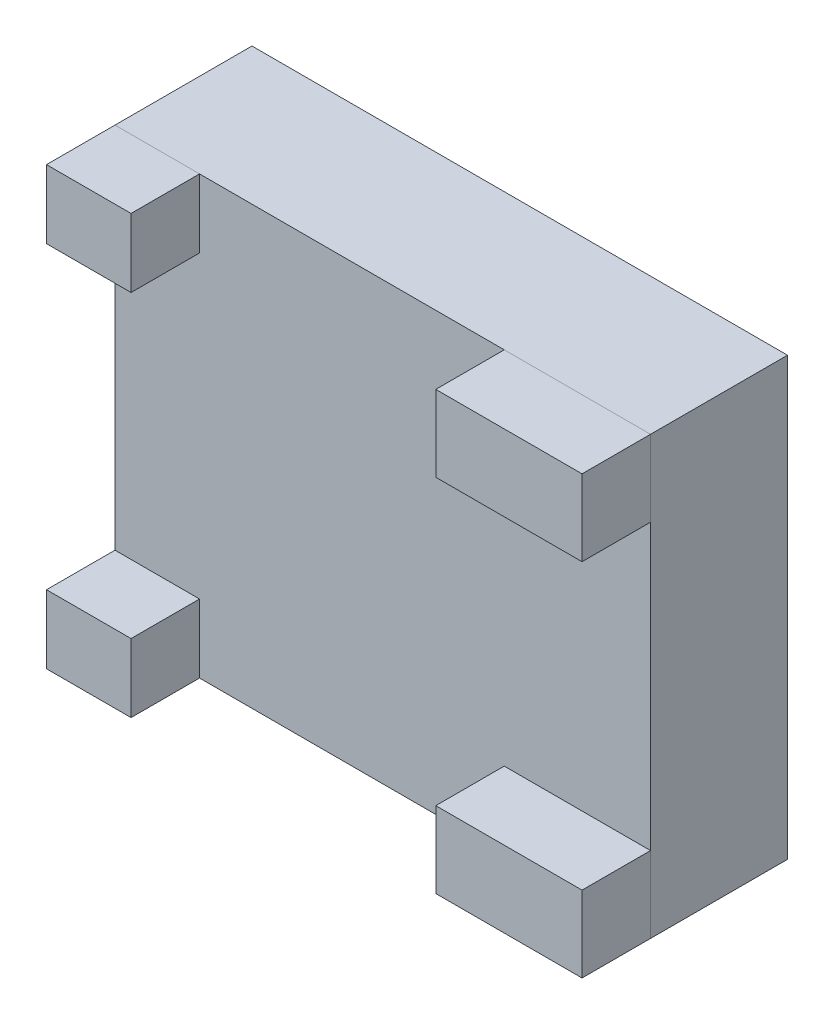
SolidWorks part; units mm, degrees
other "A"
other "B"
other "corpo 3"
other "C" parameters "Espessura"=2
material "AISI 1020"
ref_plane "Plano superior" through (0, 0, 0) normal (0, 0, 1) x (1, 0, 0)
ref_plane "Plano frontal" through (0, 0, 0) normal (0, 1, 0) x (1, 0, 0)
ref_plane "Plano direito" through (0, 0, 0) normal (1, 0, 0) x (0, 0, -1)
other "CAIXA"
ref_plane "Default Plane" through (78.1989, -63.755, 60) normal (0, 1, 0) x (1, 0, 0)
ref_plane "TOP" through (0, 0, 0) normal (0, 0, 1) x (1, 0, 0)
sketch "Esboço1" plane through (0, 0, 0) normal (0, 0, 1) x (1, 0, 0)
  line L1 (-78.1989, -63.755) -> (78.1989, -63.755)
  line L2 (-78.1989, -63.755) -> (-78.1989, 63.755)
  line L3 (-78.1989, 63.755) -> (78.1989, 63.755)
  line L4 (78.1989, -63.755) -> (78.1989, 63.755)
  line L5 (-78.1989, -63.755) -> (78.1989, 63.755) construction
  line L6 (-78.1989, 63.755) -> (78.1989, -63.755) construction
  circle A0 centre (0, 0) radius 15.125 construction
  point P0 (0, 0)
  dimension "D3" = 30.25
  dimension "D1" = 156.3979
  dimension "D2" = 127.51
extrude "Novo" add sketch "Esboço1" along normal blind 40
sketch "Esboço2" plane through (0, 0, 40) normal (0, 0, 1) x (1, 0, 0)
  line L0 (0, 0) -> (-78.1989, 0) construction
  line L1 (-78.1989, -63.755) -> (-53.5079, -63.755)
  line L2 (-78.1989, -63.755) -> (-78.1989, -43.755)
  line L3 (-78.1989, -43.755) -> (-53.5079, -43.755)
  line L4 (-53.5079, -63.755) -> (-53.5079, -43.755)
  line L5 (-78.1989, 63.755) -> (-78.1989, -63.755) construction
  line L6 (-78.1989, 43.755) -> (-53.5079, 43.755)
  line L7 (-53.5079, 63.755) -> (-53.5079, 43.755)
  line L8 (-78.1989, 63.755) -> (-53.5079, 63.755)
  line L9 (-78.1989, 63.755) -> (-78.1989, 43.755)
  line L10 (78.1989, 41.5261) -> (35.4788, 41.5261)
  line L11 (78.1989, -63.755) -> (35.4788, -63.755)
  line L12 (78.1989, -63.755) -> (78.1989, -41.5261)
  line L13 (78.1989, -41.5261) -> (35.4788, -41.5261)
  line L14 (35.4788, -63.755) -> (35.4788, -41.5261)
  line L15 (35.4788, 63.755) -> (35.4788, 41.5261)
  line L16 (78.1989, 63.755) -> (35.4788, 63.755)
  line L17 (78.1989, 63.755) -> (78.1989, 41.5261)
  dimension "D1" = 20
extrude "Ressalto-extrusão2" add sketch "Esboço2" along normal blind 20 separate body
delete or keep bodies "Corpo: A Mantido" [suppressed] type keep bodies bodies 111
delete or keep bodies "Corpo: C Mantido" [suppressed] type keep bodies bodies 114
delete or keep bodies "Corpo: B Mantido" [suppressed] type keep bodies bodies 112
